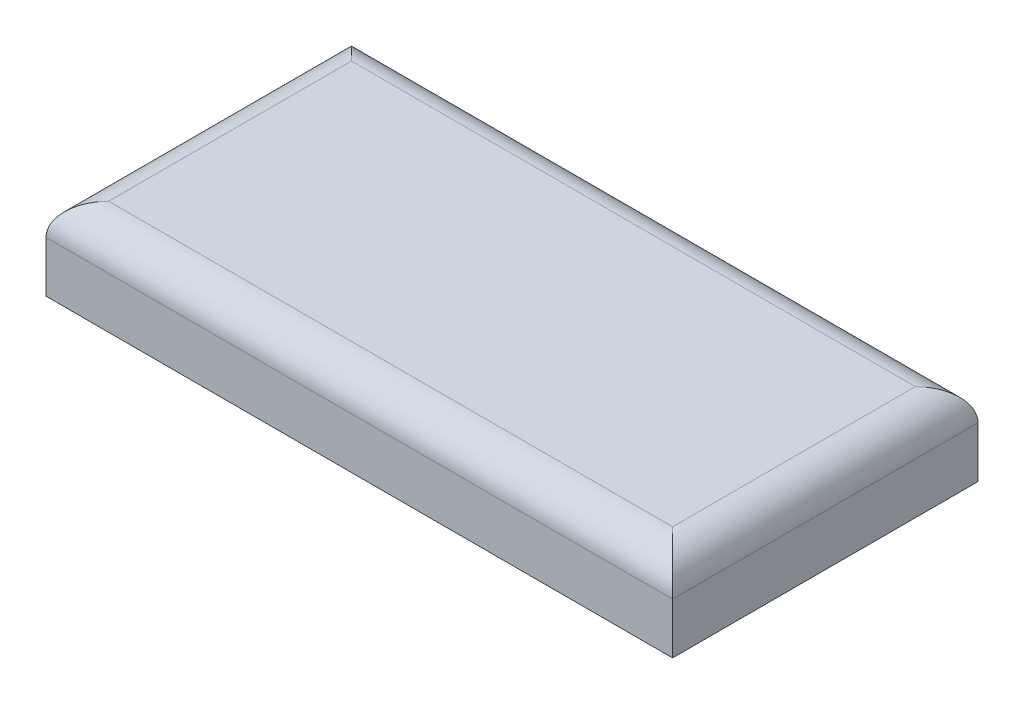
SolidWorks part; units mm, degrees
material "ABS"
ref_plane "Front Plane" through (0, 0, 0) normal (0, 0, 1) x (1, 0, 0)
ref_plane "Top Plane" through (0, 0, 0) normal (0, 1, 0) x (1, 0, 0)
ref_plane "Right Plane" through (0, 0, 0) normal (1, 0, 0) x (0, 0, -1)
sketch "Sketch1" plane through (0, 0, 0) normal (0, 1, 0) x (1, 0, 0)
  line L1 (-38.5, -18) -> (38.5, -18)
  line L2 (-38.5, -18) -> (-38.5, 18)
  line L3 (-38.5, 18) -> (38.5, 18)
  line L4 (38.5, -18) -> (38.5, 18)
  line L5 (-38.5, -18) -> (38.5, 18) construction
  line L6 (-38.5, 18) -> (38.5, -18) construction
  line L7 (40, -19.5) -> (-40, -19.5)
  line L8 (40, -19.5) -> (40, 19.5)
  line L9 (40, 19.5) -> (-40, 19.5)
  line L10 (-40, -19.5) -> (-40, 19.5)
  line L11 (40, -19.5) -> (-40, 19.5) construction
  line L12 (40, 19.5) -> (-40, -19.5) construction
  point P0 (0, 0)
  point P5 (0, 0)
  dimension "D1" = 36
  dimension "D2" = 77
  dimension "D3" = 1.5
  dimension "D4" = 1.5
extrude "Boss-Extrude1" add sketch "Sketch1" along normal blind 9
sketch "Sketch2" plane through (0, 9, 0) normal (0, 1, 0) x (1, 0, 0)
  line L1 (40, 19.5) -> (-40, 19.5)
  line L2 (40, 19.5) -> (40, -19.5)
  line L3 (40, -19.5) -> (-40, -19.5)
  line L4 (-40, 19.5) -> (-40, -19.5)
  line L5 (40, 19.5) -> (-40, -19.5) construction
  line L6 (40, -19.5) -> (-40, 19.5) construction
  point P0 (0, 0)
extrude "Boss-Extrude2" add sketch "Sketch2" along normal blind 1.5
sketch "Sketch4" plane through (0, 0, 0) normal (0, -1, 0) x (1, 0, 0)
  line L0 (-38.5, 18) -> (38.5, 18) construction
  line L1 (39.25, -18.75) -> (-39.25, -18.75)
  line L2 (39.25, -18.75) -> (39.25, 18.75)
  line L3 (39.25, 18.75) -> (-39.25, 18.75)
  line L4 (-39.25, -18.75) -> (-39.25, 18.75)
  line L5 (39.25, -18.75) -> (-39.25, 18.75) construction
  line L6 (39.25, 18.75) -> (-39.25, -18.75) construction
  line L7 (38.5, 18) -> (38.5, -18) construction
  point P0 (0, 0)
  dimension "D1" = 0.75
  dimension "D2" = 0.75
extrude "Cut-Extrude1" cut sketch "Sketch4" against normal blind 1
fillet "Fillet1" radius 4 4 edges at (0, 10.5, -19.5) (40, 10.5, 0) (0, 10.5, 19.5) (-40, 10.5, 0)
sketch "Sketch5" plane through (0, 0, -19.5) normal (0, 0, -1) x (-1, 0, 0)
  line L0 (36.5, -3) -> (36.5, 3) construction
  line L1 (-40, 0) -> (40, 0) construction
  line L2 (34.5, -3) -> (34.5, 3)
  line L3 (38.5, -3) -> (38.5, 3)
  line L5 (40, 6.5) -> (40, 0) construction
  arc A0 (34.5, -3) -> (38.5, -3) centre (36.5, -3) ccw
  arc A1 (38.5, 3) -> (34.5, 3) centre (36.5, 3) ccw
  point P4 (36.5, 0)
  point P11 (36.5, 5)
  dimension "D1" = 1.5
  dimension "D2" = 4
  dimension "D3" = 5
extrude "Cut-Extrude2" cut sketch "Sketch5" against normal up to next
